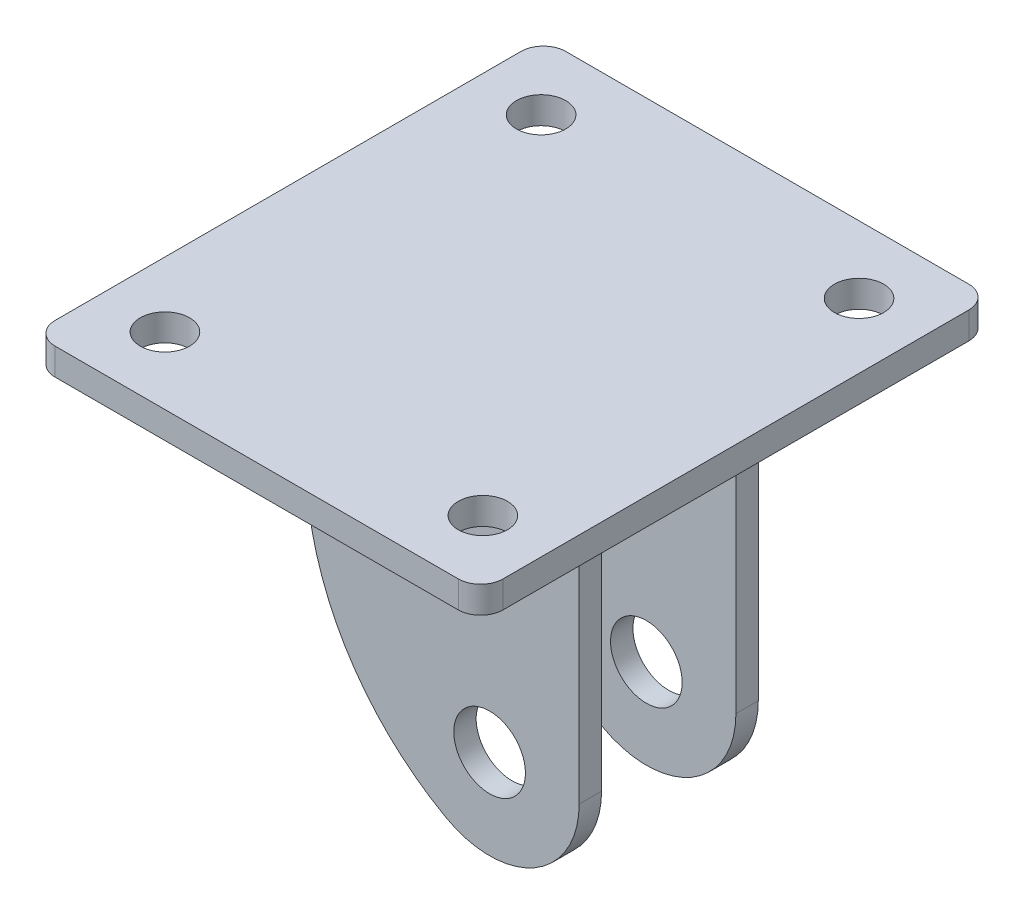
SolidWorks part; units mm, degrees
ref_plane "Front Plane" through (0, 0, 0) normal (0, 0, 1) x (1, 0, 0)
ref_plane "Top Plane" through (0, 0, 0) normal (0, 1, 0) x (1, 0, 0)
ref_plane "Right Plane" through (0, 0, 0) normal (1, 0, 0) x (0, 0, -1)
sketch "Sketch1" plane through (0, 0, 0) normal (0, 1, 0) x (1, 0, 0)
  line L1 (-45, -57) -> (45, -57)
  line L2 (-50, -52) -> (-50, 52)
  line L3 (-45, 57) -> (45, 57)
  line L4 (50, -52) -> (50, 52)
  line L5 (-50, -57) -> (50, 57) construction
  line L6 (-50, 57) -> (50, -57) construction
  arc A0 (-45, -57) -> (-50, -52) centre (-45, -52) cw
  arc A1 (50, -52) -> (45, -57) centre (45, -52) cw
  arc A2 (50, 52) -> (45, 57) centre (45, 52) ccw
  arc A3 (-45, 57) -> (-50, 52) centre (-45, 52) ccw
  point P0 (0, 0)
  point P6 (0, 0)
  dimension "D3" = 5
  dimension "D1" = 100
  dimension "D2" = 114
extrude "Boss-Extrude1" add sketch "Sketch1" along normal mid plane 6
sketch "Sketch2" plane through (0, 0, 0) normal (0, 0, 1) x (1, 0, 0)
  line L0 (-25, -3) -> (-25, -17.3389)
  line L2 (35, -64.0554) -> (35, -3)
  line L3 (-45, -3) -> (45, -3) construction
  line L4 (-25, -3) -> (35, -3)
  line L5 (50, 3) -> (50, -3) construction
  arc A0 (-25, -17.3389) -> (5.2413, -81.513) centre (35, -28.2771) ccw
  circle A1 centre (15, -64.0554) radius 8
  arc A2 (35, -64.0554) -> (5.2413, -81.513) centre (15, -64.0554) cw
  point P5 (0, 0)
  point P6 (35, -28.2771)
  point P13 (35, -89.266)
  dimension "D4" = 15
  dimension "D5" = 8
  dimension "D6" = 60.9889
  dimension "D8" = 20
  dimension "D2" = 40
  dimension "D3" = 61.0554
  dimension "D1" = 60
extrude "Boss-Extrude2" add sketch "Sketch2" against normal blind 5 from offset 20
mirror "Mirror1" about plane through (0, 0, 0) normal (0, 0, 1) of "Boss-Extrude2"
sketch "Sketch3" plane through (0, 3, 0) normal (0, 1, 0) x (1, 0, 0)
  line L0 (0, 0) -> (0, 24.4231) construction
  circle A4 centre (35.5, 42) radius 5.5
  circle A5 centre (-35.5, 42) radius 5.5
  circle A9 centre (-35.5, -42) radius 5.5
  circle A11 centre (35.5, -42) radius 5.5
  dimension "D1" = 11
  dimension "D2" = 84
  dimension "D3" = 71
  dimension "D4" = 84
  dimension "D5" = 42
  dimension "D6" = 35.5
extrude "Cut-Extrude1" cut sketch "Sketch3" against normal through all
